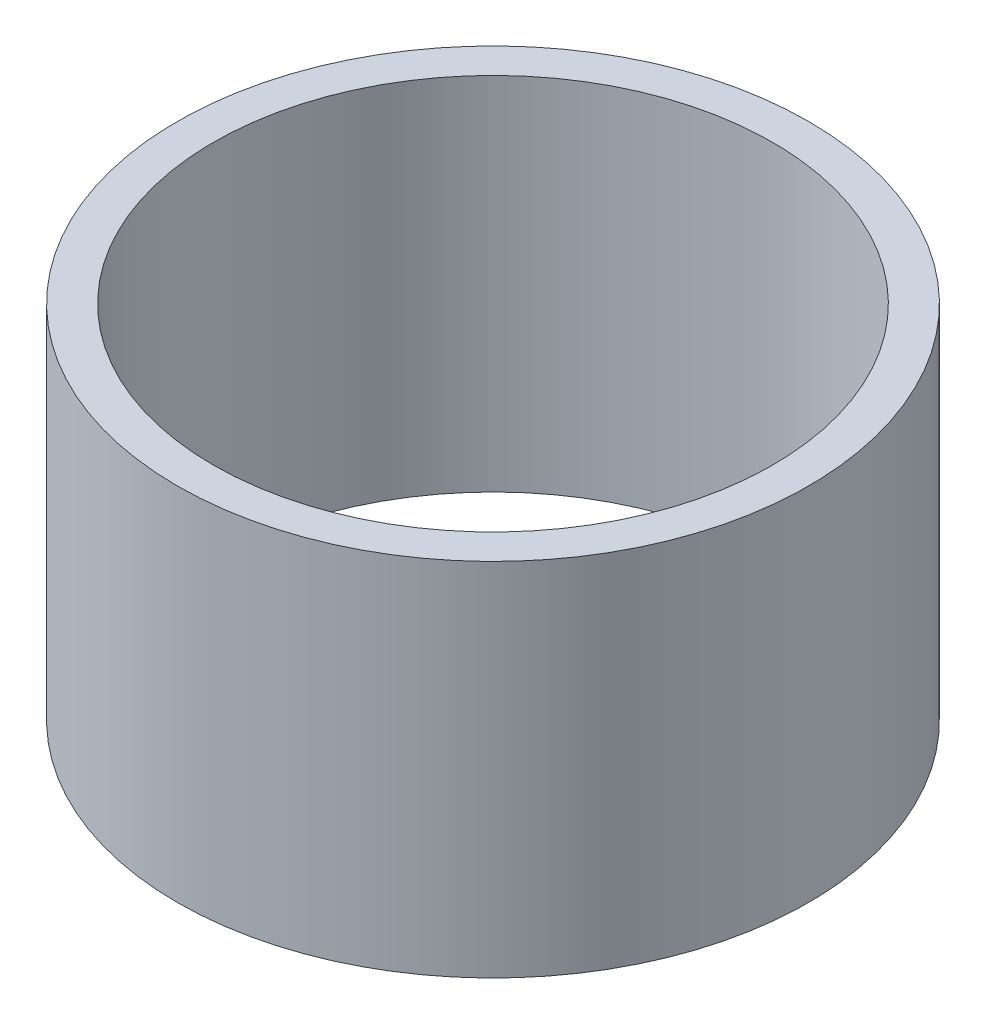
SolidWorks part; units mm, degrees
ref_plane "Front Plane" through (0, 0, 0) normal (0, 0, 1) x (1, 0, 0)
ref_plane "Top Plane" through (0, 0, 0) normal (0, 1, 0) x (1, 0, 0)
ref_plane "Right Plane" through (0, 0, 0) normal (1, 0, 0) x (0, 0, -1)
sketch "Çizim2" plane through (0, 0, 0) normal (0, 1, 0) x (1, 0, 0)
  circle A0 centre (0, 0) radius 3.1
  circle A1 centre (0, 0) radius 3.5
  dimension "D1" = 6.2
  dimension "D2" = 7
extrude "Yükseklik-Ekstrüzyon1" add sketch "Çizim2" along normal blind 4
